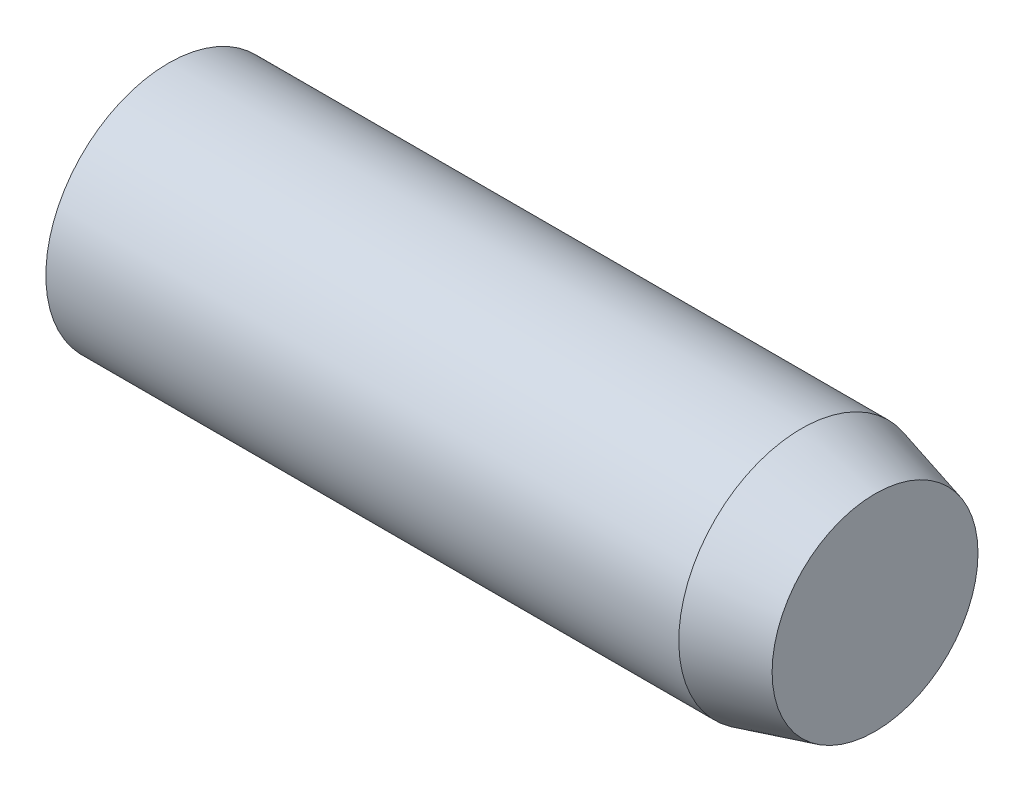
SolidWorks part; units mm, degrees
ref_plane "Plane1" through (0, 0, 0) normal (0, 0, 1) x (1, 0, 0)
ref_plane "Plane2" through (0, 0, 0) normal (0, 1, 0) x (1, 0, 0)
ref_plane "Plane3" through (0, 0, 0) normal (1, 0, 0) x (0, 0, -1)
sketch "BodySke" plane through (0, 0, 0) normal (0, 0, 1) x (1, 0, 0)
  line L0 (0, 0) -> (40.9091, 0) construction
  line L1 (27, 5) -> (30, 4.1962)
  line L2 (1.2, 5) -> (27, 5)
  line L3 (30, 4.1962) -> (30, 0)
  line L4 (0, 0) -> (30, 0)
  arc A0 (1.2, 5) -> (0, 0) centre (11.0167, 0) ccw
  dimension "D1" = 15
  dimension "Diameter" = 10
  dimension "Length" = 30
  dimension "Crown_ht" = 1.2
  dimension "Chamfer_len" = 3
revolve "Body" add sketch "BodySke" angle 360 about L0
equation "' \"D1@BodySke\" = \"Length@BodySke\""
